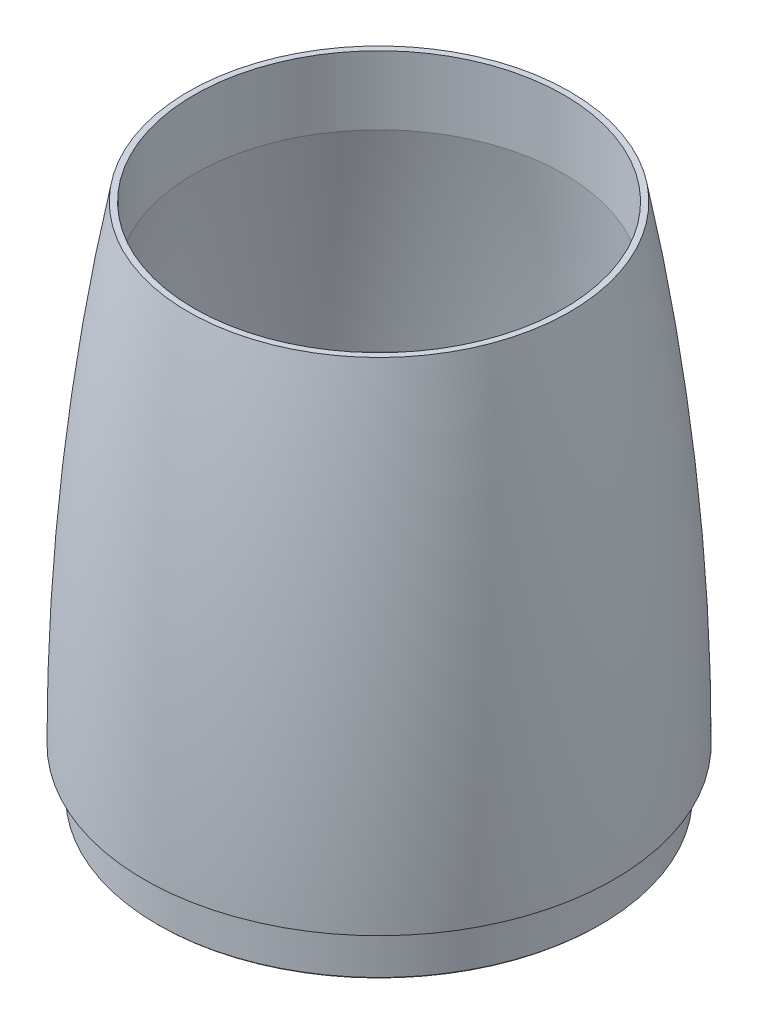
SolidWorks part; units mm, degrees
ref_plane "Front Plane" through (0, 0, 0) normal (0, 0, 1) x (1, 0, 0)
ref_plane "Top Plane" through (0, 0, 0) normal (0, 1, 0) x (1, 0, 0)
ref_plane "Right Plane" through (0, 0, 0) normal (1, 0, 0) x (0, 0, -1)
sketch "Sketch1" plane through (0, 0, 0) normal (0, 0, 1) x (1, 0, 0)
  line L0 (0, -1572.0261) -> (0, 77082.0793) construction
  line L1 (-32.5, 80) -> (-31.5, 80)
  line L2 (-31.5, 80) -> (-31.5, 68.3472)
  line L3 (0, 0) -> (-40, 0) construction
  line L4 (-40, -986.4994) -> (-40, 49013.5006) construction
  line L5 (-40, 0) -> (-37.75, 0)
  line L6 (-37.75, 0) -> (-37.75, -8)
  line L7 (-37.75, -8) -> (-35.75, -8)
  line L8 (-35.75, -8) -> (-35.75, 32.6646)
  arc A0 (-32.5, 80) -> (-40, 0) centre (390.4167, 0) ccw
  arc A1 (-31.5, 68.3472) -> (-35.75, 32.6646) centre (390.4167, 0) ccw
  point P4 (376.7782, 0)
  point P7 (576.1596, -19.3151)
  point P16 (859.6647, -46.7796)
  point P18 (0, 0)
  dimension "D2" = 3
  dimension "D1" = 80
  dimension "D3" = 63
  dimension "D4" = 1
  dimension "D5" = 80
  dimension "D6" = 75.5
  dimension "D7" = 2
  dimension "D8" = 8
revolve "Revolve1" add sketch "Sketch1" angle 360 about L0
chamfer "Chamfer1" distance 0.25 angle 45 2 edges at (0, -8, -37.75) (0, -8, -35.75)
